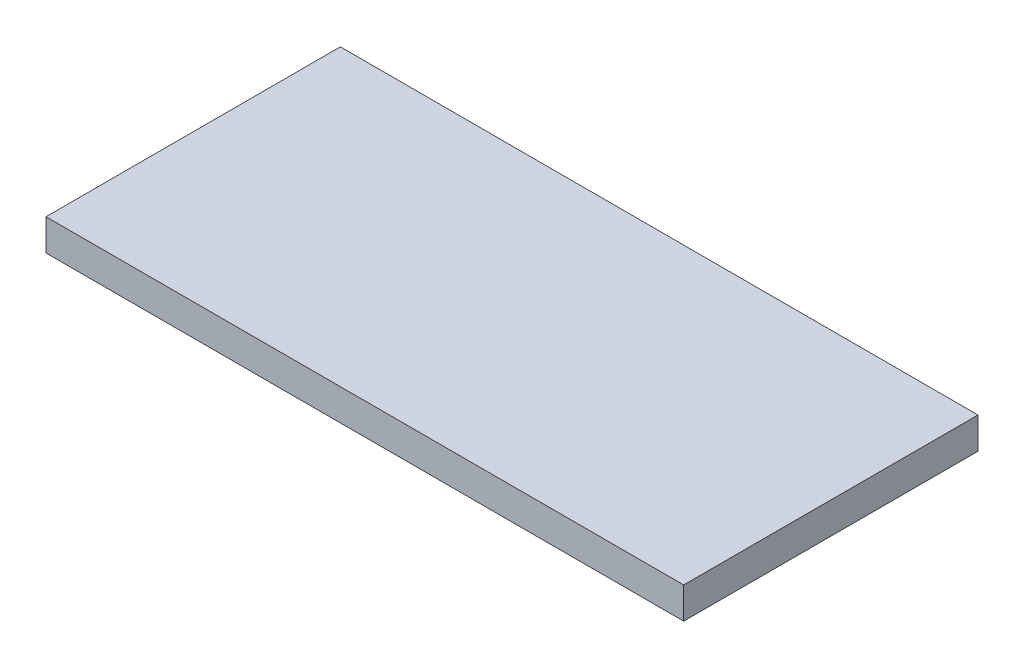
SolidWorks part; units mm, degrees
material "Plain Carbon Steel"
ref_plane "Front Plane" through (0, 0, 0) normal (0, 0, 1) x (1, 0, 0)
ref_plane "Top Plane" through (0, 0, 0) normal (0, 1, 0) x (1, 0, 0)
ref_plane "Right Plane" through (0, 0, 0) normal (1, 0, 0) x (0, 0, -1)
sketch "Sketch1" plane through (0, 0, 0) normal (0, 1, 0) x (1, 0, 0)
  line L1 (0, 0) -> (65, 0)
  line L2 (0, 0) -> (0, 30)
  line L3 (0, 30) -> (65, 30)
  line L4 (65, 0) -> (65, 30)
  dimension "D1" = 30
  dimension "D2" = 65
extrude "Boss-Extrude1" add sketch "Sketch1" along normal blind 3.2
